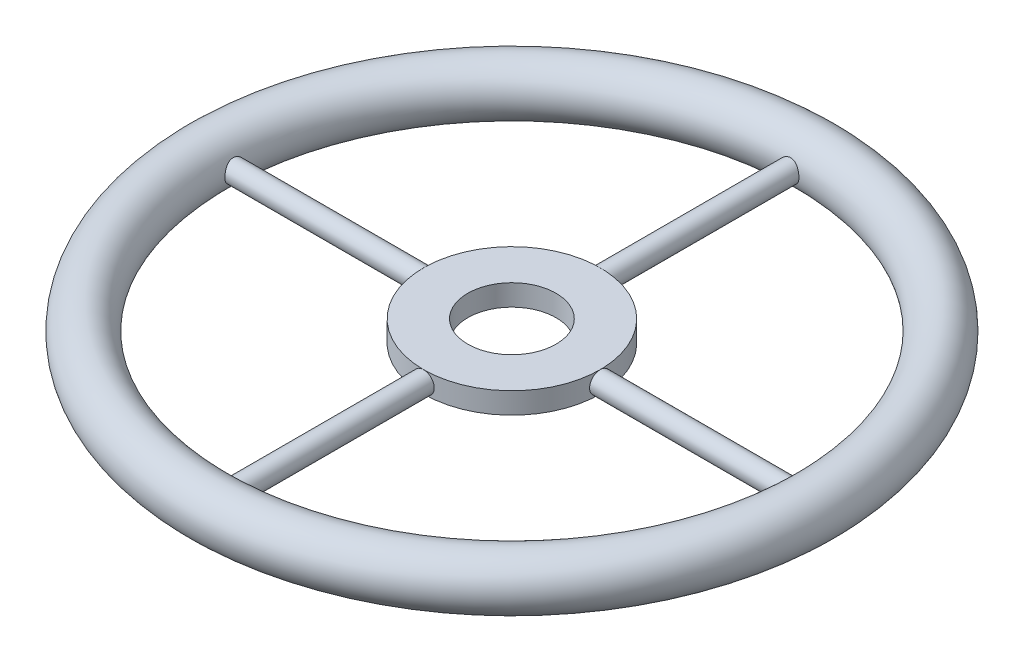
SolidWorks part; units mm, degrees
ref_plane "Front Plane" through (0, 0, 0) normal (0, 0, 1) x (1, 0, 0)
ref_plane "Top Plane" through (0, 0, 0) normal (0, 1, 0) x (1, 0, 0)
ref_plane "Right Plane" through (0, 0, 0) normal (1, 0, 0) x (0, 0, -1)
sketch "Sketch1" plane through (0, 0, 0) normal (1, 0, 0) x (0, 0, -1)
  circle A0 centre (85.8477, 0) radius 7.5
  dimension "D1" = 15
  dimension "D2" = 85.8477
sketch "Sketch6" plane through (0, 0, 0) normal (1, 0, 0) x (0, 0, -1)
  line L0 (0, 23.3152) -> (0, -21.5258) construction
revolve "Revolve1" add sketch "Sketch1" angle 360 about L0
sketch "Sketch7" plane through (0, 0, 0) normal (0, 1, 0) x (1, 0, 0)
  circle A0 centre (0, 0) radius 25
  circle A1 centre (0, 0) radius 12.5
  dimension "D1" = 50
  dimension "D2" = 25
extrude "Boss-Extrude1" add sketch "Sketch7" along normal mid plane 6 separate body
ref_plane "Plane1" through (25, 0, 0) normal (1, 0, 0) x (0, 0, -1)
sketch "Sketch9" plane through (25, 0, 0) normal (1, 0, 0) x (0, 0, -1)
  circle A0 centre (0, 0) radius 3
  dimension "D1" = 6
extrude "Boss-Extrude2" add sketch "Sketch9" along normal blind 60
pattern_circular "CirPattern1" count 4 over 360 about axis through (0, 0, 0) along (0, 1, 0) of "Boss-Extrude2"
